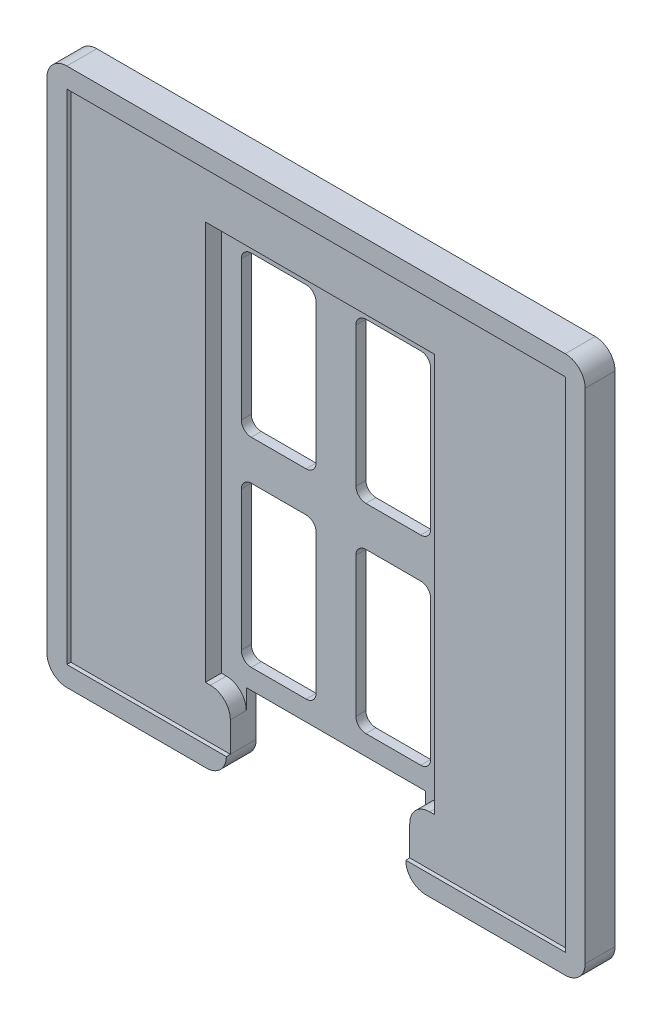
SolidWorks part; units mm, degrees
ref_plane "Спереди" through (0, 0, 0) normal (0, 0, 1) x (1, 0, 0)
ref_plane "Сверху" through (0, 0, 0) normal (0, 1, 0) x (1, 0, 0)
ref_plane "Справа" through (0, 0, 0) normal (1, 0, 0) x (0, 0, -1)
sketch "Эскиз1" plane through (0, 0, 0) normal (0, 0, 1) x (1, 0, 0)
  line L1 (-27, 27) -> (27, 27)
  line L2 (-27, 27) -> (-27, -27)
  line L3 (-27, -27) -> (27, -27)
  line L4 (27, 27) -> (27, -27)
  line L5 (-27, 27) -> (27, -27) construction
  line L6 (-27, -27) -> (27, 27) construction
  point P0 (0, 0)
  dimension "D1" = 54
  dimension "D2" = 54
extrude "Бобышка-Вытянуть1" add sketch "Эскиз1" along normal blind 3
sketch "Эскиз2" plane through (0, 0, 3) normal (0, 0, 1) x (1, 0, 0)
  line L1 (-11.5, 20) -> (11.5, 20)
  line L2 (-11.5, 20) -> (-11.5, -20)
  line L3 (-11.5, -20) -> (11.5, -20)
  line L4 (11.5, 20) -> (11.5, -20)
  line L5 (-11.5, 20) -> (11.5, -20) construction
  line L6 (-11.5, -20) -> (11.5, 20) construction
  point P0 (0, 0)
  dimension "D1" = 40
  dimension "D2" = 23
extrude "Вырез-Вытянуть1" cut sketch "Эскиз2" against normal blind 2
sketch "Эскиз3" plane through (0, 0, 3) normal (0, 0, 1) x (1, 0, 0)
  line L1 (-25, 25) -> (25, 25)
  line L2 (-25, 25) -> (-25, -25)
  line L3 (-25, -25) -> (25, -25)
  line L4 (25, 25) -> (25, -25)
  line L5 (-25, 25) -> (25, -25) construction
  line L6 (-25, -25) -> (25, 25) construction
  point P0 (0, 0)
  dimension "D1" = 50
  dimension "D2" = 50
extrude "Вырез-Вытянуть2" cut sketch "Эскиз3" against normal blind 0.4
sketch "Эскиз4" plane through (0, 0, 3) normal (0, 0, 1) x (1, 0, 0)
  line L0 (0, 0) -> (0, -43.5897) construction
  line L1 (-9, -27) -> (-9, -20)
  line L2 (-9, -27) -> (9, -27)
  line L3 (-9, -20) -> (9, -20)
  line L4 (9, -27) -> (9, -20)
  line L5 (-9, -27) -> (9, -20) construction
  line L6 (-9, -20) -> (9, -27) construction
  line L7 (11.5, -20) -> (-11.5, -20) construction
  line L8 (-27, -27) -> (27, -27) construction
  point P3 (0, 0)
  point P4 (0, -23.5)
  point P5 (0, 0)
  point P12 (0, 0)
  dimension "D1" = 18
extrude "Вырез-Вытянуть3" cut sketch "Эскиз4" against normal through all
sketch "Эскиз5" plane through (0, 0, 1) normal (0, 0, 1) x (1, 0, 0)
  line L0 (0, 0) -> (0, 36.1139) construction
  line L1 (0, 0) -> (35.5856, 0) construction
  line L2 (11.5, 20) -> (-11.5, 20) construction
  line L3 (-2, 2) -> (-9.5, 2)
  line L4 (-2, 2) -> (-2, 18)
  line L5 (-2, 18) -> (-9.5, 18)
  line L6 (-9.5, 2) -> (-9.5, 18)
  line L7 (-11.5, 20) -> (-11.5, -20) construction
  line L8 (9.5, 2) -> (9.5, 18)
  line L9 (2, 18) -> (9.5, 18)
  line L10 (2, 2) -> (2, 18)
  line L11 (2, 2) -> (9.5, 2)
  line L12 (-9.5, -2) -> (-9.5, -18)
  line L13 (-2, -18) -> (-9.5, -18)
  line L14 (-2, -2) -> (-2, -18)
  line L15 (-2, -2) -> (-9.5, -2)
  line L16 (2, -2) -> (9.5, -2)
  line L17 (2, -2) -> (2, -18)
  line L18 (2, -18) -> (9.5, -18)
  line L19 (9.5, -2) -> (9.5, -18)
  dimension "D1" = 2
  dimension "D2" = 2
  dimension "D3" = 2
  dimension "D4" = 2
extrude "Вырез-Вытянуть4" cut sketch "Эскиз5" against normal through all
fillet "Скругление1" radius 2 4 edges at (9, -27, 1.5) (9, -20, 1.8) (-9, -27, 1.5) (-9, -20, 1.8)
fillet "Скругление2" radius 1 16 edges at (-9.5, 2, 0.5) (2, 2, 0.5) (-2, 2, 0.5) (9.5, 2, 0.5) (2, 18, 0.5) (9.5, 18, 0.5) (-2, 18, 0.5) (-9.5, 18, 0.5) (2, -18, 0.5) (9.5, -18, 0.5) (-2, -18, 0.5) (-9.5, -18, 0.5) (2, -2, 0.5) (9.5, -2, 0.5) (-2, -2, 0.5) (-9.5, -2, 0.5)
fillet "Скругление3" radius 2 4 edges at (-27, -27, 1.5) (27, -27, 1.5) (27, 27, 1.5) (-27, 27, 1.5)
